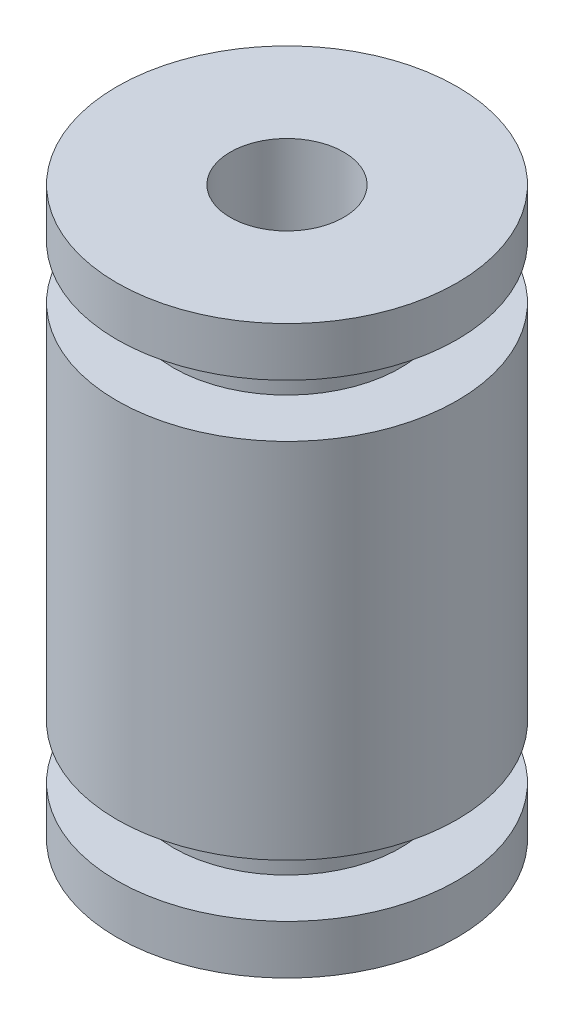
SolidWorks part; units mm, degrees
ref_plane "Alzado" through (0, 0, 0) normal (0, 0, 1) x (1, 0, 0)
ref_plane "Planta" through (0, 0, 0) normal (0, 1, 0) x (1, 0, 0)
ref_plane "Vista lateral" through (0, 0, 0) normal (1, 0, 0) x (0, 0, -1)
sketch "Croquis1" plane through (0, 0, 0) normal (0, 0, 1) x (1, 0, 0)
  line L0 (0, 0) -> (0, 7.5) construction
  line L1 (-1.5, 7.5) -> (-1.5, -7.5)
  line L2 (-1.5, 7.5) -> (-4.5, 7.5)
  line L3 (-4.5, 7.5) -> (-4.5, 6.2)
  line L4 (-4.5, 6.2) -> (-3, 6.2)
  line L5 (-3, 6.2) -> (-3, 4.8)
  line L6 (-3, 4.8) -> (-4.5, 4.8)
  line L7 (-4.5, 4.8) -> (-4.5, -4.8)
  line L8 (-4.5, 0) -> (-1.5, 0) construction
  line L9 (-3, -4.8) -> (-4.5, -4.8)
  line L10 (-3, -6.2) -> (-3, -4.8)
  line L11 (-4.5, -6.2) -> (-3, -6.2)
  line L12 (-4.5, -7.5) -> (-4.5, -6.2)
  line L13 (-1.5, -7.5) -> (-4.5, -7.5)
  dimension "D1" = 7.5
  dimension "D2" = 1.3
  dimension "D3" = 1.4
  dimension "D4" = 3
  dimension "D5" = 4.5
  dimension "D6" = 1.5
revolve "Revolución1" add sketch "Croquis1" angle 360 about L0
